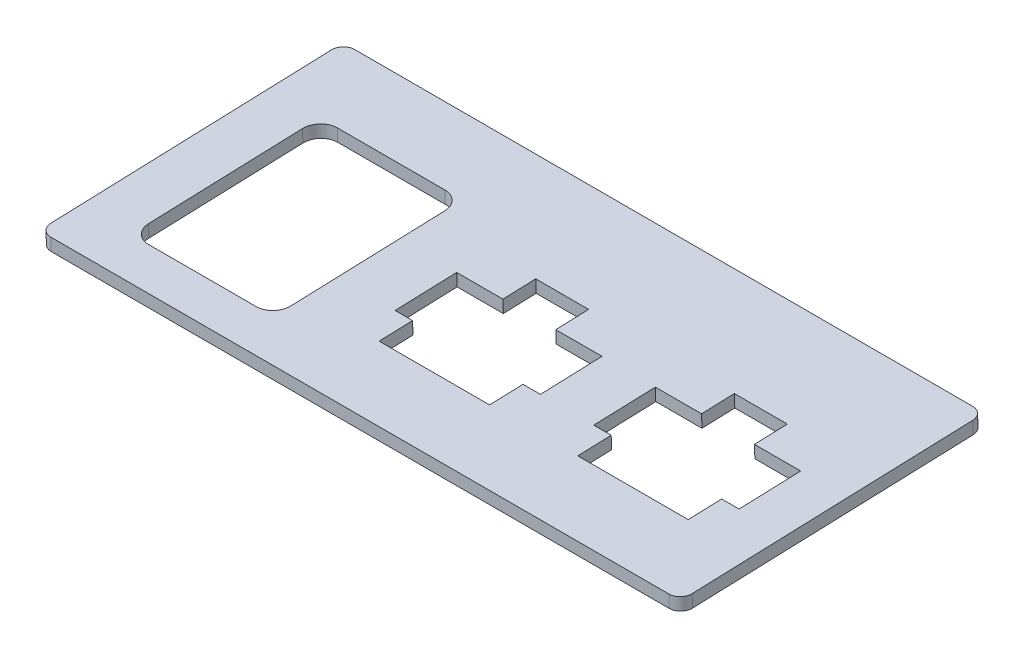
SolidWorks part; units mm, degrees
ref_plane "Front Plane" through (0, 0, 0) normal (0, 0, 1) x (1, 0, 0)
ref_plane "Top Plane" through (0, 0, 0) normal (0, 1, 0) x (1, 0, 0)
ref_plane "Right Plane" through (0, 0, 0) normal (1, 0, 0) x (0, 0, -1)
sketch "Sketch1" plane through (0, -71.9872, -2.5138) normal (0, 0.9994, 0.0349) x (1, 0, 0)
  line L0 (-56.175, 48.6398) -> (56.175, 48.6398) construction
  line L1 (-52.175, -2.9116) -> (-56.175, -2.9116) construction
  line L8 (-55.175, -4.4116) -> (55.175, -4.4116)
  line L9 (55.175, -4.4116) -> (55.175, 47.8898)
  line L10 (55.175, 47.8898) -> (-55.175, 47.8898)
  line L11 (-55.175, 47.8898) -> (-55.175, -4.4116)
  dimension "D4" = 0.75
  dimension "D1" = 1.5
  dimension "D2" = 3.0034
  dimension "D3" = 3.0034
extrude "Boss-Extrude1" add sketch "Sketch1" along normal blind 2.2
sketch "Sketch2" plane through (0, -71.9872, -2.5138) normal (0, -0.9994, -0.0349) x (1, 0, 0)
  line L0 (-4.05, -24.2621) -> (-4.05, -29.9121)
  line L1 (-43.425, -2.6621) -> (-24.925, -2.6621)
  line L2 (-46.425, -5.6621) -> (-46.425, -32.1621)
  line L3 (-43.425, -35.1621) -> (-24.925, -35.1621)
  line L4 (-21.925, -5.6621) -> (-21.925, -32.1621)
  line L5 (-12, -13.6621) -> (-9, -13.6621)
  line L6 (-12, -13.6621) -> (-12, -24.2621)
  line L7 (-12, -24.2621) -> (-4.05, -24.2621)
  line L8 (13, -13.6621) -> (13, -24.2621)
  line L9 (-9, -7.9121) -> (10, -7.9121)
  line L10 (-9, -7.9121) -> (-9, -13.6621)
  line L11 (-4.05, -29.9121) -> (5.05, -29.9121)
  line L12 (10, -7.9121) -> (10, -13.6621)
  line L13 (10, -13.6621) -> (13, -13.6621)
  line L14 (5.05, -24.2621) -> (5.05, -29.9121)
  line L15 (5.05, -24.2621) -> (13, -24.2621)
  line L16 (-13, -5.4121) -> (14, -32.4121) construction
  line L17 (-13, -5.4121) -> (14, -5.4121) construction
  line L18 (-13, -5.4121) -> (-13, -32.4121) construction
  line L19 (-13, -32.4121) -> (14, -32.4121) construction
  line L20 (14, -5.4121) -> (14, -32.4121) construction
  line L21 (17.5875, 3.7502) -> (17.5875, -36.664) construction
  line L22 (47.175, -18.9621) -> (22.175, -18.9621) construction
  line L23 (34.675, -7.9121) -> (34.675, -29.9121) construction
  line L24 (21.175, -5.4121) -> (21.175, -32.4121) construction
  line L25 (48.175, -32.4121) -> (21.175, -32.4121) construction
  line L26 (48.175, -5.4121) -> (48.175, -32.4121) construction
  line L27 (48.175, -5.4121) -> (21.175, -5.4121) construction
  line L28 (-48.175, -18.9121) -> (-46.425, -18.9121) construction
  line L29 (-48.175, -0.9121) -> (-20.175, -0.9121) construction
  line L30 (-48.175, -0.9121) -> (-48.175, -36.9121) construction
  line L31 (-48.175, -36.9121) -> (-20.175, -36.9121) construction
  line L32 (-20.175, -0.9121) -> (-20.175, -36.9121) construction
  line L33 (-34.175, -2.6621) -> (-34.175, -0.9121) construction
  line L34 (0.5, -7.9121) -> (0.5, -29.9121) construction
  line L35 (-12, -18.9621) -> (13, -18.9621) construction
  line L36 (48.175, -5.4121) -> (21.175, -32.4121) construction
  line L37 (30.125, -24.2621) -> (22.175, -24.2621)
  line L38 (30.125, -24.2621) -> (30.125, -29.9121)
  line L39 (25.175, -13.6621) -> (22.175, -13.6621)
  line L40 (25.175, -7.9121) -> (25.175, -13.6621)
  line L41 (39.225, -29.9121) -> (30.125, -29.9121)
  line L42 (44.175, -7.9121) -> (44.175, -13.6621)
  line L43 (44.175, -7.9121) -> (25.175, -7.9121)
  line L44 (22.175, -13.6621) -> (22.175, -24.2621)
  line L45 (47.175, -24.2621) -> (39.225, -24.2621)
  line L46 (47.175, -13.6621) -> (47.175, -24.2621)
  line L47 (47.175, -13.6621) -> (44.175, -13.6621)
  line L48 (39.225, -24.2621) -> (39.225, -29.9121)
  line L49 (21.175, -18.9121) -> (14, -18.9121) construction
  line L51 (48.175, -18.9121) -> (52.175, -18.9121) construction
  line L52 (55.175, 4.4116) -> (55.175, -47.8898) construction
  line L53 (-46.7914, -40.6398) -> (46.7914, -40.6398) construction
  line L54 (-13, -18.9121) -> (-20.175, -18.9121) construction
  line L55 (-34.175, -0.9121) -> (-34.175, 2.8156) construction
  line L56 (-34.175, -36.9121) -> (-34.175, -40.6398) construction
  line L57 (-55.175, -47.8898) -> (-55.175, 4.4116) construction
  line L58 (-48.175, -18.9121) -> (-52.175, -18.9121) construction
  line L59 (-53.075, 2.8156) -> (53.075, 2.8156) construction
  arc A0 (-46.425, -32.1621) -> (-43.425, -35.1621) centre (-43.425, -32.1621) ccw
  arc A1 (-24.925, -35.1621) -> (-21.925, -32.1621) centre (-24.925, -32.1621) ccw
  arc A2 (-24.925, -2.6621) -> (-21.925, -5.6621) centre (-24.925, -5.6621) cw
  arc A3 (-43.425, -2.6621) -> (-46.425, -5.6621) centre (-43.425, -5.6621) ccw
  point P28 (0.5, -18.9121)
  point P63 (34.675, -18.9121)
  dimension "D1" = 3
  dimension "D2" = 32.5
  dimension "D3" = 24.5
  dimension "D4" = 28
  dimension "D5" = 36
  dimension "D6" = 25
  dimension "D7" = 22
  dimension "D8" = 10.6
  dimension "D9" = 19
  dimension "D10" = 9.1
  dimension "D11" = 5.75
  dimension "D12" = 27
  dimension "D13" = 27
  dimension "D14" = 4
  dimension "D15" = 3
  dimension "D16" = 3
extrude "Cut-Extrude1" cut sketch "Sketch2" against normal up to next
fillet "Fillet1" radius 2 4 edges at (-55.175, -71.0418, 1.9334) (55.175, -71.0418, 1.9334) (55.175, -69.2165, -50.336) (-55.175, -69.2165, -50.336)
